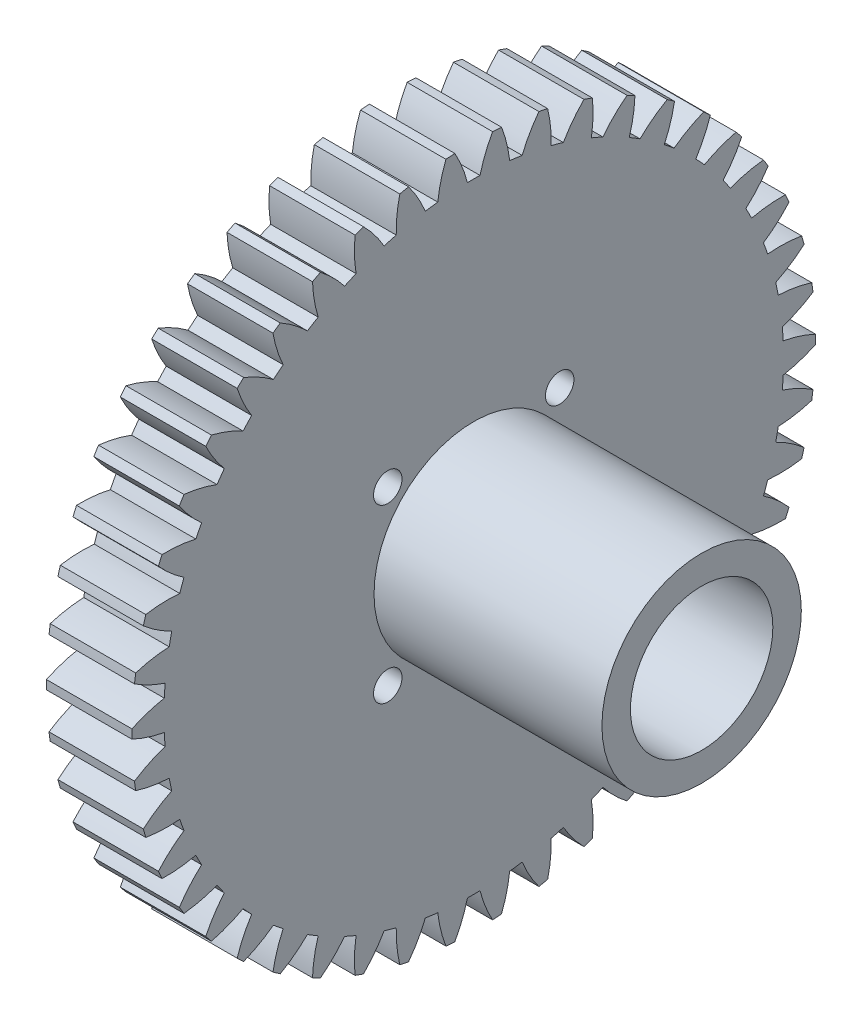
SolidWorks part; units mm, degrees
ref_plane "Plane1" through (0, 0, 0) normal (0, 0, 1) x (1, 0, 0)
ref_plane "Plane2" through (0, 0, 0) normal (0, 1, 0) x (1, 0, 0)
ref_plane "Plane3" through (0, 0, 0) normal (1, 0, 0) x (0, 0, -1)
other "Configuration Table"
sketch "HoldingSke" plane through (0, 0, 0) normal (0, 1, 0) x (1, 0, 0)
  line L0 (0, 0) -> (0.6947, -0.7193)
  line L1 (-15, 0) -> (100, 0) construction
  line L2 (0, 0) -> (-2.1039, 2.3779)
  line L3 (0, 0) -> (-11.863, 4.5341)
  line L4 (0, 0) -> (5.9991, 6.2122)
  line L5 (0, 0) -> (-46.8476, -17.4728)
  line L6 (0, 0) -> (-4.9738, -3.3558)
  line L7 (-2.1039, 2.3779) -> (8.6586, 51.206)
  line L8 (-76.2, 54.61) -> (-75.2, 54.61)
  line L9 (-71.009, 38.7566) -> (-53.1078, 45.2721)
  line L10 (-76.2, 71.12) -> (104.1128, 71.12)
  line L11 (0, 0) -> (-6, 0)
  line L12 (-76.2, 101.6) -> (-76.162, 101.6)
  line L13 (24.9733, 27.94) -> (52.9518, 28.4284)
  line L14 (24.9733, 27.94) -> (24.9743, 27.94)
  line L15 (24.9733, 27.94) -> (100.4006, 29.5858)
  line L16 (-63.627, -1) -> (-12.827, -1)
  circle A0 centre (0, 0) radius 3
  circle A1 centre (0, 0) radius 21.749
  circle A2 centre (0, 0) radius 37.5
  circle A3 centre (0, 0) radius 3
  dimension "MHD" = 43.498
  dimension "Hub_dia" = 75
  dimension "Bore" = 6
  dimension "MBD" = 6
  dimension "Num_teeth" = 46
  dimension "Pitch" = 1
  dimension "Overall_len" = 50
  dimension "Show_teeth" = 46
  dimension "Thickness" = 6
  dimension "OAL" = 50.0002
  dimension "T_dim" = 1
  dimension "Ap" = 20
  dimension "H" = 19.05
  dimension "Pitch_radius" = 180.3128
  dimension "Width" = 6
  dimension "Backlash" = 0.038
  dimension "Addendum_fac" = 1
  dimension "Dedendum_fac" = 1.25
  dimension "Clearance_fac" = 0.25
  dimension "Dedendum_add" = 0.001
  dimension "Module" = 1
sketch "BasProSke" plane through (0, 0, 0) normal (0, 1, 0) x (1, 0, 0)
  line L0 (-10, 0) -> (60, 0) construction
  line L1 (0, 0) -> (0, 24)
  line L2 (0, 0) -> (6, 0)
  line L3 (6, 0) -> (6, 24)
  line L4 (6, 24) -> (0, 24)
  dimension "Thickness" = 6
  dimension "Diameter" = 48
revolve "Base-Revolve" add sketch "BasProSke" angle 360 about L0
sketch "TooCutSke" plane through (0, 0, 0) normal (1, 0, 0) x (0, 0, -1)
  line L1 (0, 0) -> (0, 107) construction
  line L2 (0, 0) -> (-0.8517, 22.9842) construction
  line L3 (0, 0) -> (-3.1376, 45.8703) construction
  line L4 (-0.8517, 22.9842) -> (-1.5688, 22.9352) construction
  arc A0 (0.4415, 21.7445) -> (-0.4415, 21.7445) centre (0, 0) ccw
  arc A1 (1.3382, 23.9881) -> (-1.3382, 23.9881) centre (0, 0) ccw
  circle A2 centre (0, 0) radius 23 construction
  circle A3 centre (0, 0) radius 21.6129 construction
  arc A4 (-0.4415, 21.7445) -> (-1.3382, 23.9881) centre (-9.3589, 19.4815) ccw
  arc A5 (1.3382, 23.9881) -> (0.4415, 21.7445) centre (9.3589, 19.4815) ccw
  dimension "Root_dia" = 43.498
  dimension "Overcut_dia" = 48.0508
  dimension "Pitch_dia" = 46
  dimension "Base_dia" = 43.2259
  dimension "Flank_rad" = 9.2
  dimension "Half_ang" = 3.913
  dimension "Half_CT" = 0.7187
extrude "ToothCut" cut sketch "TooCutSke" along normal through all
fillet "Breaks" [suppressed] radius 0.02
fillet "RootFillets" [suppressed] radius 0.251
pattern_circular "TeethCuts" count 46 every 7.826 about axis through (-10, 0, 0) along (1, 0, 0) of "ToothCut", "RootFillets", "Breaks"
sketch "HubNeaOneSke" plane through (0, 0, 0) normal (-1, 0, 0) x (0, 0, 1)
  circle A0 centre (0, 0) radius 21.749
  dimension "Diameter" = 43.498
extrude "HubNearOne" [suppressed] add sketch "HubNeaOneSke" along normal blind 44.0002
sketch "HubNeaBotSke" plane through (0, 0, 0) normal (-1, 0, 0) x (0, 0, 1)
  circle A0 centre (0, 0) radius 21.749
  dimension "Diameter" = 43.498
extrude "HubNearBoth" [suppressed] add sketch "HubNeaBotSke" along normal blind 22.0001
ref_plane "FarPln" through (6, 0, 0) normal (1, 0, 0) x (0, 0, -1)
sketch "HubFarSke" plane through (6, 0, 0) normal (1, 0, 0) x (0, 0, -1)
  circle A0 centre (0, 0) radius 21.749
  dimension "Diameter" = 43.498
extrude "HubFar" [suppressed] add sketch "HubFarSke" along normal blind 22.0001
sketch "KeySke" plane through (0, 0, 0) normal (1, 0, 0) x (0, 0, -1)
  line L0 (-1, 0) -> (-1, 4)
  line L1 (-1, 4) -> (1, 4)
  line L2 (1, 4) -> (1, 0)
  line L3 (0, 0) -> (0, 34) construction
  line L4 (-1, 0) -> (1, 0)
  dimension "Offset" = 4
  dimension "Width" = 2
extrude "Keyway" [suppressed] cut sketch "KeySke" along normal mid plane 100.0004
pattern_circular "Keyway2" [suppressed] count 2 every 90 about axis through (-10, 0, 0) along (1, 0, 0)
sketch "Sketch1" plane through (6, 0, 0) normal (1, 0, 0) x (0, 0, -1)
  circle A0 centre (-6.035, 6.035) radius 1
  circle A1 centre (6.035, 6.035) radius 1
  circle A2 centre (6.035, -6.035) radius 1
  circle A3 centre (-6.035, -6.035) radius 1
  dimension "D1" = 2
  dimension "D2" = 6.035
  dimension "D3" = 6.035
  dimension "D4" = 2
  dimension "D5" = 2
extrude "Cut-Extrude1" cut sketch "Sketch1" against normal through all
sketch "Sketch2" plane through (6, 0, 0) normal (1, 0, 0) x (0, 0, -1)
  circle A0 centre (0, 0) radius 5
  circle A1 centre (0, 0) radius 7
  dimension "D1" = 10
  dimension "D2" = 14
extrude "Boss-Extrude1" add sketch "Sketch2" along normal blind 16
equation "' \"Module@HoldingSke\" = 6.35"
equation "' \"Num_teeth@HoldingSke\" = 12"
equation "' \"Ap@HoldingSke\" =  20"
equation "' \"Ap@HoldingSke\" = 20"
equation "' \"Width@HoldingSke\" = 0.5 * 25.4"
equation "' \"Hub_dia@HoldingSke\"= 1 * 25.4"
equation "' \"Hub_dia@HoldingSke\" = 1 * 25.4"
equation "' \"Overall_len@HoldingSke\" = 1.0 * 25.4"
equation "' \"Bore@HoldingSke\" = 0.75 * 25.4"
equation "' \"T_dim@HoldingSke\" = 0.1 * 25.4"
equation "' \"Width@KeySke\" = 0.25 * 25.4"
equation "' \"Show_teeth@HoldingSke\" = 13"
equation "' \"Backlash@HoldingSke\" = 0.009 * 25.4"
equation "' \"Addendum_fac@HoldingSke\" = 1.0"
equation "' \"Dedendum_fac@HoldingSke\" = 1.25"
equation "' \"Dedendum_add@HoldingSke\" = 0.00005 * 25.4"
equation "' \"Clearance_fac@HoldingSke\" = 0.25"
equation "\"Pitch@HoldingSke\" = 1 / \"Module@HoldingSke\""
equation "\"Overcut_dia@TooCutSke\" = (\"Num_teeth@HoldingSke\" + 2 * \"Addendum_fac@HoldingSke\") / \"Pitch@HoldingSke\" + 0.002 * 25.4"
equation "\"Pitch_dia@TooCutSke\" = \"Num_teeth@HoldingSke\" / \"Pitch@HoldingSke\""
equation "\"Base_dia@TooCutSke\" = \"Num_teeth@HoldingSke\" / \"Pitch@HoldingSke\" * cos((\"Ap@HoldingSke\"  * 3.14159265 / 180))"
equation "\"Root_dia@TooCutSke\" = (\"Num_teeth@HoldingSke\" + 2) / \"Pitch@HoldingSke\" - 2 * (\"Addendum_fac@HoldingSke\" + \"Dedendum_fac@HoldingSke\") / \"Pitch@HoldingSke\" - \"Dedendum_add@HoldingSke\" * 2"
equation "\"Half_ang@TooCutSke\" = 180 / \"Num_teeth@HoldingSke\""
equation "\"Half_CT@TooCutSke\" = \"Num_teeth@HoldingSke\" / \"Pitch@HoldingSke\" * sin((3.14159265 / 2 / \"Num_teeth@HoldingSke\")) / 2 - 7 * \"Backlash@HoldingSke\" / 4"
equation "\"Flank_rad@TooCutSke\" = \"Num_teeth@HoldingSke\" / \"Pitch@HoldingSke\" / 5"
equation "\"Radius@RootFillets\" = \"Clearance_fac@HoldingSke\" / \"Pitch@HoldingSke\" + \"Dedendum_add@HoldingSke\""
equation "\"Break_rad@Breaks\" = 0.02 / \"Pitch@HoldingSke\""
equation "\"Thickness@HoldingSke\" = \"Width@HoldingSke\""
equation "\"OAL@HoldingSke\" = \"Thickness@HoldingSke\""
equation "\"MHD@HoldingSke\" = (\"Num_teeth@HoldingSke\" + 2) / \"Pitch@HoldingSke\" - 2 * (\"Addendum_fac@HoldingSke\" + \"Dedendum_fac@HoldingSke\")  / \"Pitch@HoldingSke\" - \"Dedendum_add@HoldingSke\" * 2"
equation "\"MBD@HoldingSke\" = (\"Num_teeth@HoldingSke\" + 2) / \"Pitch@HoldingSke\" - 2 * (\"Addendum_fac@HoldingSke\" + \"Dedendum_fac@HoldingSke\")  / \"Pitch@HoldingSke\" - \"Dedendum_add@HoldingSke\" * 2 - 0.002 * 25.4"
equation "\"MHD@HoldingSke\" = ((sgn( \"MHD@HoldingSke\" - \"Hub_dia@HoldingSke\" )-1)*( \"MHD@HoldingSke\" - \"Hub_dia@HoldingSke\" ))/-2+ \"Hub_dia@HoldingSke\""
equation "\"MBD@HoldingSke\" = ((sgn( \"MBD@HoldingSke\" - \"Bore@HoldingSke\" )-1)*( \"MBD@HoldingSke\" - \"Bore@HoldingSke\" ))/-2+ \"Bore@HoldingSke\""
equation "\"OAL@HoldingSke\" = ((sgn( \"OAL@HoldingSke\" - \"Overall_len@HoldingSke\" )+1)*( \"OAL@HoldingSke\" - \"Overall_len@HoldingSke\" ))/2 + \"Overall_len@HoldingSke\" + 0.000002 * 25.4"
equation "\"Num_teeth@TeethCuts\" = int( \"Show_teeth@HoldingSke\" ) + 1"
equation "\"Num_teeth@TeethCuts\" = ((sgn( \"Num_teeth@TeethCuts\" - \"Num_teeth@HoldingSke\" )-1)*( \"Num_teeth@TeethCuts\" - \"Num_teeth@HoldingSke\" ))/-2+ \"Num_teeth@HoldingSke\""
equation "\"Num_teeth@TeethCuts\" = ((sgn( \"Num_teeth@TeethCuts\" - 2.0)+1)*( \"Num_teeth@TeethCuts\" - 2.0))/2 +2.0"
equation "\"Angle@TeethCuts\" = 360.0 / \"Num_teeth@HoldingSke\""
equation "\"Diameter@BasProSke\" = (\"Num_teeth@HoldingSke\" + 2 * \"Addendum_fac@HoldingSke\") / \"Pitch@HoldingSke\""
equation "\"Thickness@BasProSke\"  = \"Thickness@HoldingSke\""
equation "' \"Fillet_rad@BasProSke\" =  \"Thickness@HoldingSke\" * 0.05"
equation "' \"Fillet_rad@BasProSke\" = \"Thickness@HoldingSke\" * 0.05"
equation "\"MHD@HoldingSke\" = ((sgn( \"MHD@HoldingSke\" - \"Root_dia@TooCutSke\" )-1)*( \"MHD@HoldingSke\" - \"Root_dia@TooCutSke\" ))/-2+ \"Root_dia@TooCutSke\""
equation "\"Diameter@HubNeaOneSke\" = \"MHD@HoldingSke\""
equation "\"Length@HubNearOne\" = \"OAL@HoldingSke\" - \"Thickness@BasProSke\""
equation "\"Diameter@HubNeaBotSke\" = \"MHD@HoldingSke\""
equation "\"Length@HubNearBoth\" = ( \"OAL@HoldingSke\" - \"Thickness@BasProSke\" ) / 2.0"
equation "\"Thickness@FarPln\" = \"Thickness@BasProSke\""
equation "\"Diameter@HubFarSke\" = \"MHD@HoldingSke\""
equation "\"Length@HubFar\" = ( \"OAL@HoldingSke\" - \"Thickness@BasProSke\" ) / 2.0"
equation "\"D1@Keyway\"= \"OAL@HoldingSke\" * 2.0"
equation "\"Offset@KeySke\" = \"T_dim@HoldingSke\" + \"MBD@HoldingSke\" / 2.0"
